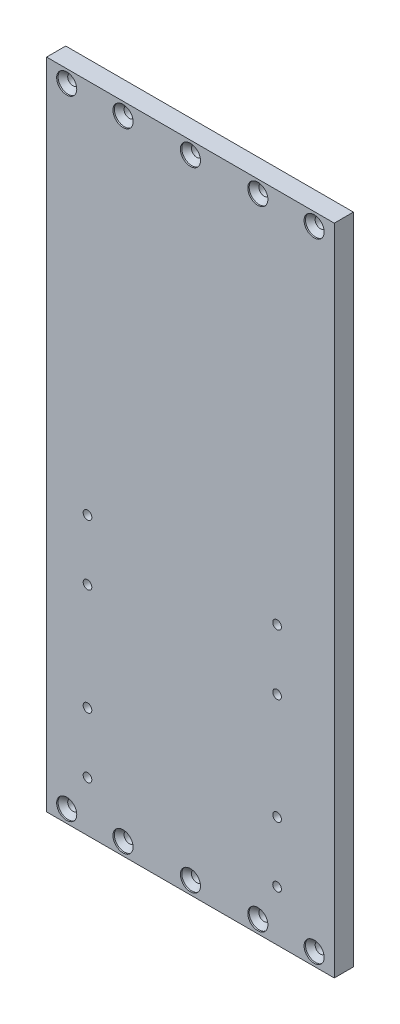
SolidWorks part; units mm, degrees
material "Aleación 1060"
ref_plane "Plano frontal" through (0, 0, 0) normal (0, 0, 1) x (1, 0, 0)
ref_plane "Plano superior" through (0, 0, 0) normal (0, 1, 0) x (1, 0, 0)
ref_plane "Plano direito" through (0, 0, 0) normal (1, 0, 0) x (0, 0, -1)
sketch "Esboço1" plane through (0, 0, 0) normal (0, 0, 1) x (1, 0, 0)
  line L0 (71.505, 162.5) -> (-71.505, -162.5) construction
  line L1 (-71.505, 162.5) -> (71.505, 162.5)
  line L2 (-71.505, 162.5) -> (-71.505, -162.5)
  line L3 (-71.505, -162.5) -> (71.505, -162.5)
  line L4 (71.505, 162.5) -> (71.505, -162.5)
  dimension "D1" = 143.01
  dimension "D2" = 325
extrude "Ressalto-extrusão1" add sketch "Esboço1" along normal blind 9.52
sketch "Esboço3" plane through (0, 0, 9.52) normal (0, 0, 1) x (1, 0, 0)
  line L0 (30.1745, -80.995) -> (-44.1621, -80.995) construction
  line L1 (-2.895, -50.8742) -> (-2.895, -107.5) construction
  line L2 (-51.175, -107.5) -> (-51.175, -137.5) construction
  line L3 (-51.175, -54.49) -> (-51.175, -24.49) construction
  line L4 (43.075, -107.4) -> (43.075, -137.4) construction
  line L7 (-71.505, -162.5) -> (71.505, -162.5) construction
  line L8 (71.505, -162.5) -> (71.505, 162.5) construction
  circle A0 centre (-51.175, -24.49) radius 2.15
  circle A1 centre (-51.175, -54.49) radius 2.15
  circle A2 centre (-51.175, -107.5) radius 2.15
  circle A3 centre (-51.175, -137.5) radius 2.15
  circle A4 centre (43.075, -137.4) radius 2.15
  circle A5 centre (43.075, -107.4) radius 2.15
  circle A6 centre (43.075, -54.59) radius 2.15
  circle A7 centre (43.075, -24.59) radius 2.15
  dimension "D2" = 25.1
  dimension "D3" = 28.43
  dimension "D4" = 55.1
  dimension "D5" = 4.3
  dimension "D6" = 48.28
  dimension "D7" = 4.3
  dimension "D8" = 4.3
  dimension "D12" = 4.3
  dimension "D9" = 25
  dimension "D10" = 55
  dimension "D11" = 81.505
  dimension "D13" = 20.33
extrude "Corte-extrusão2" cut sketch "Esboço3" against normal blind 10
sketch "Esboço4" plane through (0, 0, 0) normal (0, 0, -1) x (-1, 0, 0)
  line L0 (-71.505, 0) -> (0, 0) construction
  line L3 (-71.505, -156.15) -> (-61.505, -156.15) construction
  line L4 (-71.505, -162.5) -> (-71.505, 162.5) construction
  line L5 (-61.505, -156.15) -> (-33.505, -156.15) construction
  line L6 (-33.505, -156.15) -> (0, -156.15) construction
  line L7 (0, -156.15) -> (33.505, -156.15) construction
  line L8 (33.505, -156.15) -> (61.505, -156.15) construction
  line L9 (61.505, -156.15) -> (71.505, -156.15) construction
  line L10 (71.505, 162.5) -> (71.505, -162.5) construction
  line L11 (71.505, -162.5) -> (-71.505, -162.5) construction
  circle A0 centre (61.505, 156.15) radius 2.6
  circle A1 centre (33.505, 156.15) radius 2.6
  circle A2 centre (0, 156.15) radius 2.6
  circle A3 centre (61.505, -156.15) radius 2.6
  circle A4 centre (0, -156.15) radius 2.6
  circle A5 centre (-61.505, -156.15) radius 2.6
  circle A6 centre (-33.505, 156.15) radius 2.6
  circle A7 centre (-61.505, 156.15) radius 2.6
  circle A8 centre (33.505, -156.15) radius 2.6
  circle A9 centre (-33.505, -156.15) radius 2.6
  dimension "D1" = 5.2
  dimension "D2" = 5.2
  dimension "D3" = 5.2
  dimension "D7" = 6.35
  dimension "D15" = 5.2
  dimension "D16" = 5.2
  dimension "D10" = 71.505
  dimension "D13" = 10
  dimension "D14" = 10
  dimension "D17" = 28
  dimension "D18" = 28
extrude "Corte-extrusão3" cut sketch "Esboço4" against normal up to surface (9.52 mm away) up to face at (45.225, -24.59, 9.52)
sketch "Esboço5" plane through (0, 0, 0) normal (0, 0, -1) x (-1, 0, 0)
  line L0 (-54.7908, -80.995) -> (53.8959, -80.995) construction
  line L1 (2.895, -58.4133) -> (2.895, -113.5982) construction
  line L2 (51.175, -107.5) -> (51.175, -137.5) construction
  line L3 (71.505, -162.5) -> (-71.505, -162.5) construction
  line L4 (-43.075, -24.49) -> (-43.075, -54.49) construction
  line L5 (-43.075, -54.49) -> (-43.075, -107.4) construction
  line L6 (51.175, -107.5) -> (51.175, -137.5) construction
  line L7 (-43.075, -107.4) -> (-43.075, -137.4) construction
  line L8 (-71.505, -162.5) -> (-71.505, 162.5) construction
  circle A0 centre (51.175, -24.49) radius 4
  circle A1 centre (51.175, -54.49) radius 4
  circle A2 centre (-43.075, -54.59) radius 4
  circle A3 centre (-43.075, -24.59) radius 4
  circle A4 centre (-43.075, -137.4) radius 4
  circle A5 centre (-43.075, -107.4) radius 4
  circle A6 centre (51.175, -107.5) radius 4
  circle A7 centre (51.175, -137.5) radius 4
  dimension "D1" = 8
  dimension "D2" = 8
  dimension "D3" = 20.33
  dimension "D4" = 48.28
  dimension "D5" = 81.505
  dimension "D6" = 25
  dimension "D7" = 55
  dimension "D8" = 28.43
  dimension "D11" = 8
  dimension "D12" = 8
  dimension "D9" = 25.1
  dimension "D10" = 55.1
extrude "Corte-extrusão4" cut sketch "Esboço5" against normal blind 0.7
sketch "Esboço8" plane through (0, 0, 9.52) normal (0, 0, 1) x (1, 0, 0)
  line L0 (0, 0) -> (0, 162.7449) construction
  line L1 (71.505, 162.5) -> (-71.505, 162.5) construction
  line L2 (0, 0) -> (25.5779, 0) construction
  line L3 (72.0669, 156.15) -> (-15.9906, 156.15) construction
  circle A0 centre (-61.505, 156.15) radius 5
  circle A1 centre (-33.505, 156.15) radius 5
  circle A2 centre (0, 156.15) radius 5
  circle A3 centre (-61.505, -156.15) radius 5
  circle A4 centre (-33.505, -156.15) radius 5
  circle A5 centre (33.505, 156.15) radius 5
  circle A6 centre (61.505, 156.15) radius 5
  circle A7 centre (0, -156.15) radius 5
  circle A8 centre (33.505, -156.15) radius 5
  circle A9 centre (61.505, -156.15) radius 5
  dimension "D1" = 10
  dimension "D2" = 10
  dimension "D3" = 10
  dimension "D4" = 10
  dimension "D5" = 38
  dimension "D6" = 6.35
extrude "Corte-extrusão6" cut sketch "Esboço8" against normal blind 0.7
sketch "Croquis2" plane through (0, 0, 8.82) normal (0, 0, 1) x (1, 0, 0)
  line L0 (-48.7749, 0) -> (53.2628, 0) construction
  line L2 (71.4086, 156.15) -> (0, 156.15) construction
  line L4 (71.505, 162.5) -> (-71.505, 162.5) construction
  line L5 (71.505, -162.5) -> (71.505, 162.5) construction
  circle A1 centre (61.505, 156.15) radius 5
  circle A2 centre (33.505, 156.15) radius 5
  circle A3 centre (0, 156.15) radius 5
  circle A4 centre (-61.505, 156.15) radius 5
  circle A5 centre (-33.505, 156.15) radius 5
  circle A6 centre (61.505, -156.15) radius 5
  circle A7 centre (33.505, -156.15) radius 5
  circle A8 centre (0, -156.15) radius 5
  circle A9 centre (-33.505, -156.15) radius 5
  circle A10 centre (-61.505, -156.15) radius 5
  dimension "D1" = 6.35
  dimension "D4" = 10
  dimension "D5" = 10
  dimension "D6" = 10
  dimension "D2" = 10
  dimension "D3" = 38
extrude "Cortar-Extruir2" cut sketch "Croquis2" against normal blind 2.5 draft 45
sketch "Croquis3" plane through (0, 0, 0.7) normal (0, 0, -1) x (-1, 0, 0)
  circle A0 centre (51.175, -137.5) radius 4
  circle A1 centre (51.175, -107.5) radius 4
  circle A2 centre (-43.075, -137.4) radius 4
  circle A3 centre (-43.075, -107.4) radius 4
  circle A4 centre (-43.075, -54.59) radius 4
  circle A5 centre (-43.075, -24.59) radius 4
  circle A6 centre (51.175, -54.49) radius 4
  circle A7 centre (51.175, -24.49) radius 4
extrude "Cortar-Extruir3" cut sketch "Croquis3" against normal blind 2 draft 45
